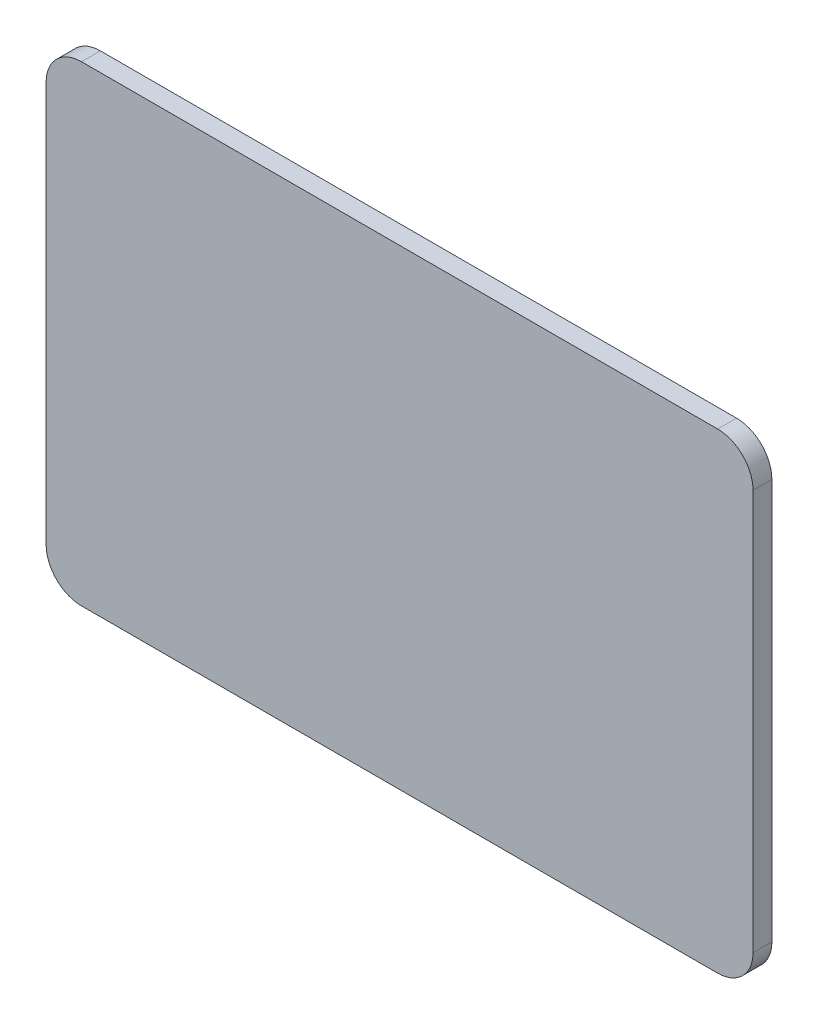
SolidWorks part; units mm, degrees
material "Q235A"
ref_plane "前视" through (0, 0, 0) normal (0, 0, 1) x (1, 0, 0)
ref_plane "上视" through (0, 0, 0) normal (0, 1, 0) x (1, 0, 0)
ref_plane "右视" through (0, 0, 0) normal (1, 0, 0) x (0, 0, -1)
sketch "草图1" plane through (0, 0, 0) normal (0, 0, 1) x (1, 0, 0)
  line L1 (300, -200) -> (-300, -200)
  line L2 (300, -200) -> (300, 200)
  line L3 (300, 200) -> (-300, 200)
  line L4 (-300, -200) -> (-300, 200)
  line L5 (300, -200) -> (-300, 200) construction
  line L6 (300, 200) -> (-300, -200) construction
  point P0 (0, 0)
  dimension "D1" = 400
  dimension "D2" = 600
extrude "凸台-拉伸1" add sketch "草图1" along normal blind 16
fillet "圆角1" radius 30 4 edges at (300, -200, 8) (300, 200, 8) (-300, -200, 8) (-300, 200, 8)
